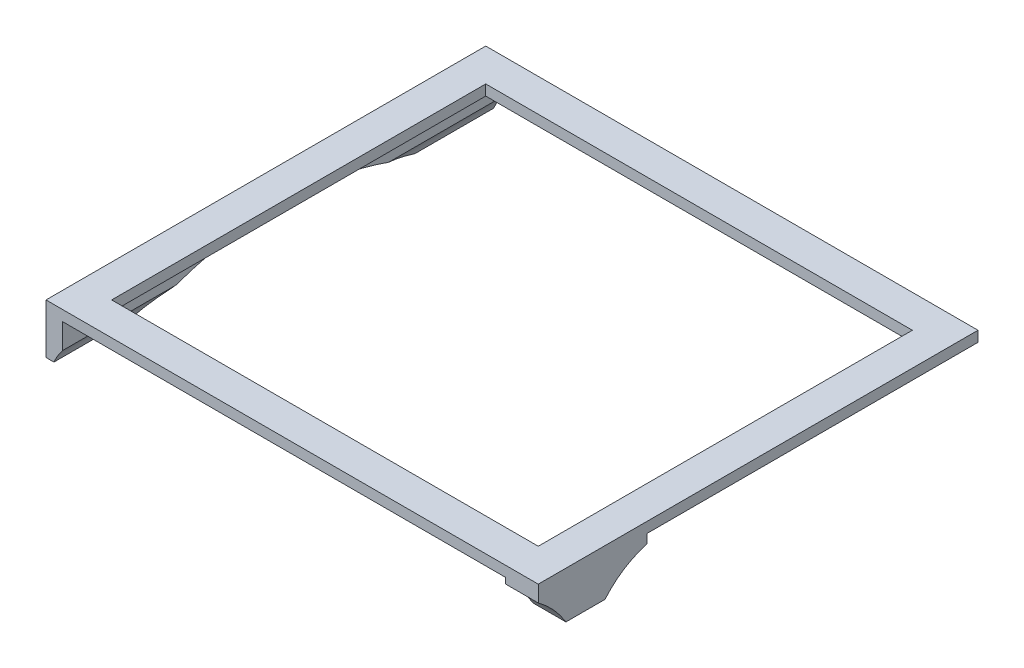
SolidWorks part; units mm, degrees
ref_plane "Front Plane" through (0, 0, 0) normal (0, 0, 1) x (1, 0, 0)
ref_plane "Top Plane" through (0, 0, 0) normal (0, 1, 0) x (1, 0, 0)
ref_plane "Right Plane" through (0, 0, 0) normal (1, 0, 0) x (0, 0, -1)
sketch "Sketch1" plane through (0, 0, 0) normal (0, 1, 0) x (1, 0, 0)
  line L0 (70, 5) -> (70, 62)
  line L1 (0, 0) -> (75, 0)
  line L2 (0, 0) -> (0, 67)
  line L3 (0, 67) -> (75, 67)
  line L4 (75, 0) -> (75, 67)
  line L5 (5, 62) -> (70, 62)
  line L6 (5, 5) -> (5, 62)
  line L7 (5, 5) -> (70, 5)
  dimension "D1" = 67
  dimension "D2" = 75
  dimension "D3" = 5
extrude "Boss-Extrude1" add sketch "Sketch1" along normal blind 1.6
sketch "Sketch2" plane through (0, 0, 0) normal (0, -1, 0) x (-1, 0, 0)
  line L5 (-70, 5) -> (-70, 62) construction
  line L6 (-75, 0) -> (-70, 0)
  line L7 (-75, 0) -> (-75, 16.5536)
  line L8 (-75, 16.5536) -> (-70, 16.5536)
  line L9 (-70, 0) -> (-70, 16.5536)
extrude "Boss-Extrude2" add sketch "Sketch2" along normal blind 5.5
sketch "Sketch3" plane through (0, 0, 0) normal (0, -1, 0) x (-1, 0, 0)
  line L0 (0, 0) -> (-70, 0) construction
  line L1 (0, 67) -> (-2.5, 67)
  line L2 (0, 67) -> (0, 0)
  line L3 (0, 0) -> (-2.5, 0)
  line L4 (-2.5, 67) -> (-2.5, 0)
  dimension "D1" = 2.5
extrude "Boss-Extrude3" add sketch "Sketch3" along normal blind 6
sketch "Sketch4" plane through (0, 0, 0) normal (0, 0, 1) x (1, 0, 0)
  line L0 (2.5, -6) -> (2.5, 0) construction
  line L1 (2.5, -6) -> (0, -6) construction
  line L2 (2.5, -3.8431) -> (2.5, -6)
  line L3 (2.5, -6) -> (1.2084, -6)
  arc A0 (2.5, -3.8431) -> (1.2084, -6) centre (9.5, -9.5) ccw
  dimension "D1" = 7
  dimension "D2" = 18
  dimension "D3" = 3.5
extrude "Cut-Extrude1" cut sketch "Sketch4" against normal up to next
sketch "Sketch5" plane through (0, 0, 0) normal (-1, 0, 0) x (0, 0, 1)
  line L0 (0, -6) -> (-67, -6) construction
  line L1 (-67, 1.6) -> (-67, -6) construction
  line L2 (0, 1.6) -> (0, -6) construction
  line L4 (-12, -6) -> (-55, -6)
  spline S0 degree 2 poles (-55, -6) (-33.5, 4) (-12, -6) knots 0 0 0 1 1 1
  point P10 (-33.5, -6)
  dimension "D1" = 12
  dimension "D2" = 12
  dimension "D3" = 5
extrude "Cut-Extrude2" cut sketch "Sketch5" against normal up to next
sketch "Sketch6" plane through (75, 0, 0) normal (1, 0, 0) x (0, 0, -1)
  line L0 (0, 1.6) -> (0, -5.5) construction
  line L1 (16.5536, -5.5) -> (0, -5.5) construction
  line L2 (16.5536, -5.5) -> (16.5536, 0) construction
  line L3 (16.5536, -1.3776) -> (16.5536, -5.5)
  line L4 (16.5536, -5.5) -> (10.1688, -5.5)
  line L5 (4.2158, -5.5) -> (0, -5.5)
  line L6 (0, -5.5) -> (0, -0.8809)
  arc A1 (0, -0.8809) -> (4.2158, -5.5) centre (-9.3249, -13.6251) cw
  arc A2 (16.5536, -1.3776) -> (10.1688, -5.5) centre (20.1259, -13.916) ccw
  point P12 (-9.3249, -13.6251)
  point P17 (20.1259, -13.916)
extrude "Cut-Extrude3" cut sketch "Sketch6" against normal up to next
